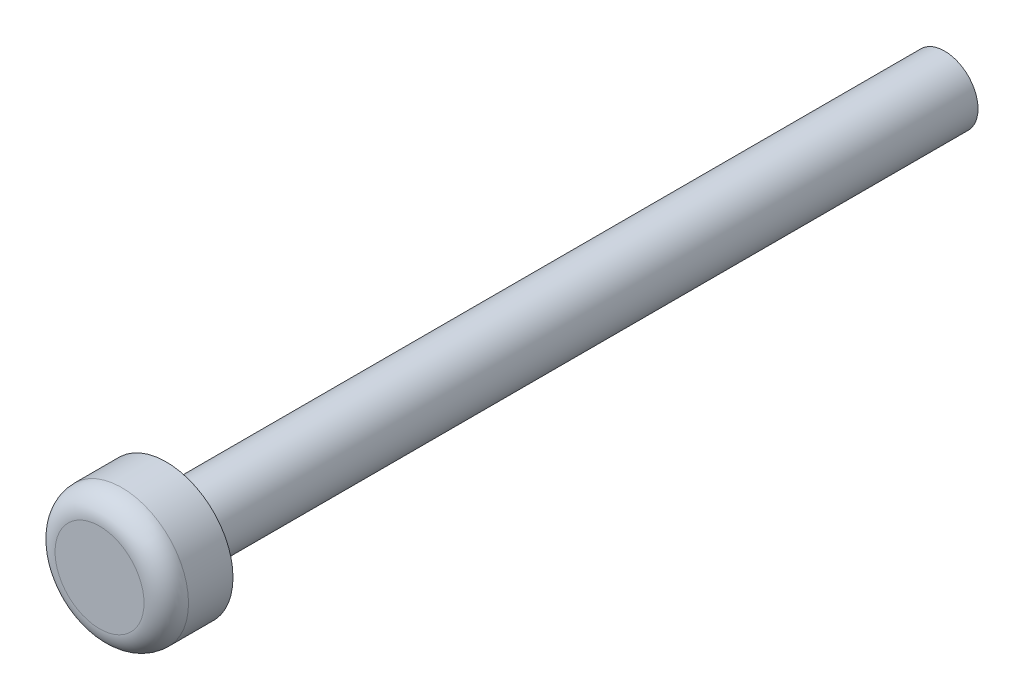
SolidWorks part; units mm, degrees
ref_plane "Front Plane" through (0, 0, 0) normal (0, 0, 1) x (1, 0, 0)
ref_plane "Top Plane" through (0, 0, 0) normal (0, 1, 0) x (1, 0, 0)
ref_plane "Right Plane" through (0, 0, 0) normal (1, 0, 0) x (0, 0, -1)
sketch "Sketch1" plane through (0, 0, 0) normal (0, 0, 1) x (1, 0, 0)
  circle A1 centre (0, 0) radius 1.5
extrude "Boss-Extrude1" add sketch "Sketch1" against normal blind 35
sketch "Sketch2" plane through (0, 0, 0) normal (0, 0, 1) x (1, 0, 0)
  circle A0 centre (0, 0) radius 3
extrude "Boss-Extrude2" add sketch "Sketch2" along normal blind 3
fillet "Fillet1" radius 1 1 edges at (3, 0, 3)
